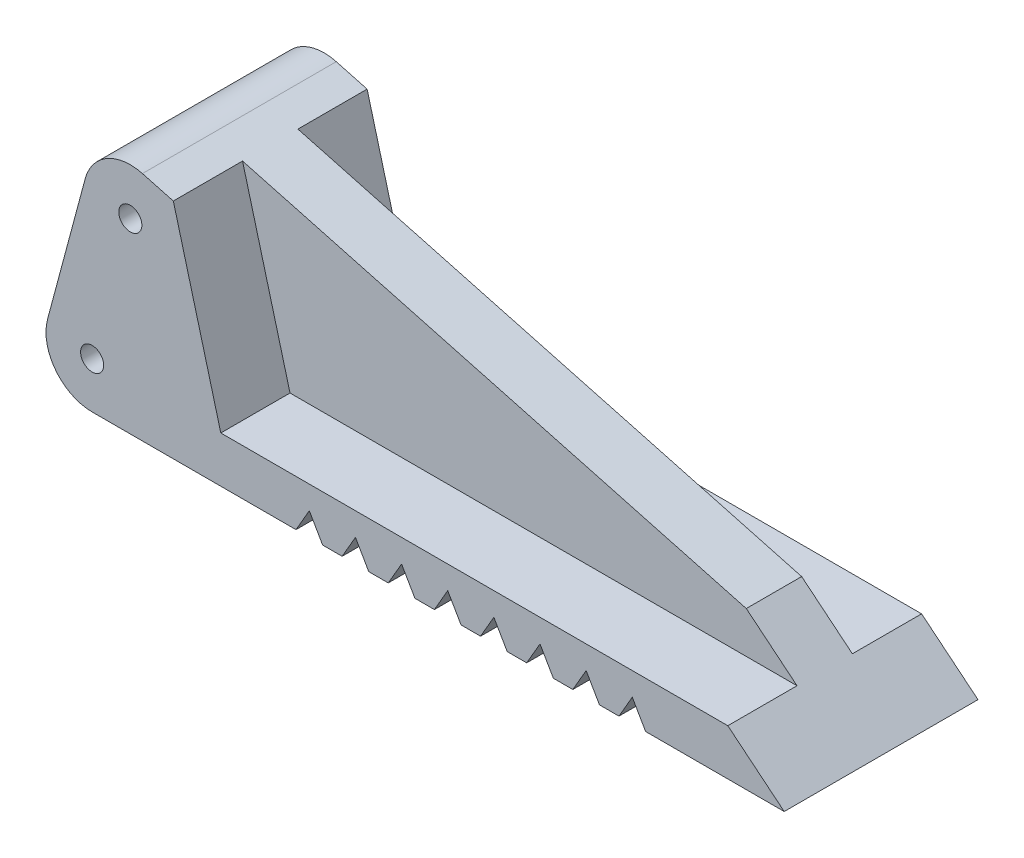
SolidWorks part; units mm, degrees
ref_plane "前视基准面" through (0, 0, 0) normal (0, 0, 1) x (1, 0, 0)
ref_plane "上视基准面" through (0, 0, 0) normal (0, 1, 0) x (1, 0, 0)
ref_plane "右视基准面" through (0, 0, 0) normal (1, 0, 0) x (0, 0, -1)
sketch "草图1" plane through (0, 0, 0) normal (0, 0, 1) x (1, 0, 0)
  line L0 (218.5025, 68.0484) -> (210.3407, 37.5882)
  line L1 (220, 25) -> (358.5479, 25)
  line L3 (230.9086, 75.2007) -> (346.7804, 43.9961)
  line L4 (346.7804, 43.9961) -> (370, 25)
  line L5 (370, 25) -> (358.5479, 25)
  circle A0 centre (220, 35) radius 2.5 construction
  circle A1 centre (228.2772, 65.4293) radius 2.5 construction
  circle A2 centre (220, 35) radius 2.5
  circle A3 centre (228.2772, 65.4293) radius 2.5
  arc A4 (220, 25) -> (210.3407, 37.5882) centre (220, 35) cw
  arc A7 (230.9086, 75.2007) -> (218.5025, 68.0484) centre (228.2772, 65.4293) ccw
  point P15 (370, 25)
  dimension "D6" = 10
  dimension "D7" = 120
  dimension "D5" = 20.2389
  dimension "D1" = 150
  dimension "D2" = 75
  dimension "D3" = 10
  dimension "D4" = 10
  dimension "D8" = 30
extrude "凸台-拉伸1" add sketch "草图1" along normal mid plane 42
sketch "草图2" plane through (0, 0, 0) normal (0, 0, 1) x (1, 0, 0)
  line L0 (220, 50) -> (205, 50)
  line L1 (205, 50) -> (205.0783, 33.4698)
  line L2 (205.0783, 33.4698) -> (205.0783, 20)
  line L3 (205.0783, 20) -> (235, 20)
  line L4 (235, 20) -> (235, 35)
  arc A0 (205.0644, 36.3888) -> (205.0783, 33.4698) centre (220, 35) ccw
  arc A1 (235, 35) -> (220, 50) centre (220, 35) ccw
extrude "切除-拉伸1" cut sketch "草图2" against normal mid plane 22 contours L4 A1 L0 L1 L2 L3
sketch "草图3" plane through (0, 0, 21) normal (0, 0, 1) x (1, 0, 0)
  line L0 (237.5998, 73.3987) -> (247.8887, 35)
  line L1 (346.7804, 43.9961) -> (230.9086, 75.2007) construction
  line L2 (247.8887, 35) -> (366.824, 35)
  line L3 (366.824, 35) -> (338.3861, 70.3337)
  line L4 (338.3861, 70.3337) -> (237.5998, 73.3987)
  line L5 (220, 25) -> (370, 25) construction
  dimension "D1" = 10
  dimension "D2" = 105
extrude "切除-拉伸2" cut sketch "草图3" against normal blind 15
mirror "镜向1" about plane through (0, 0, 0) normal (0, 0, 1) of "切除-拉伸2"
sketch "草图4" plane through (0, 0, 0) normal (0, 0, 1) x (1, 0, 0)
  line L0 (262.0719, 21.3397) -> (267.0719, 30)
  line L1 (267.0719, 30) -> (272.0719, 21.3397)
  line L2 (262.0719, 21.3397) -> (272.0719, 21.3397)
  line L3 (220, 25) -> (370, 25) construction
  dimension "D1" = 10
  dimension "D2" = 10
  dimension "D3" = 10
  dimension "D4" = 5
extrude "切除-拉伸3" cut sketch "草图4" against normal mid plane 50
pattern_linear "阵列(线性)1" count 8 spacing 10 along (1, 0, 0) of "切除-拉伸3"
